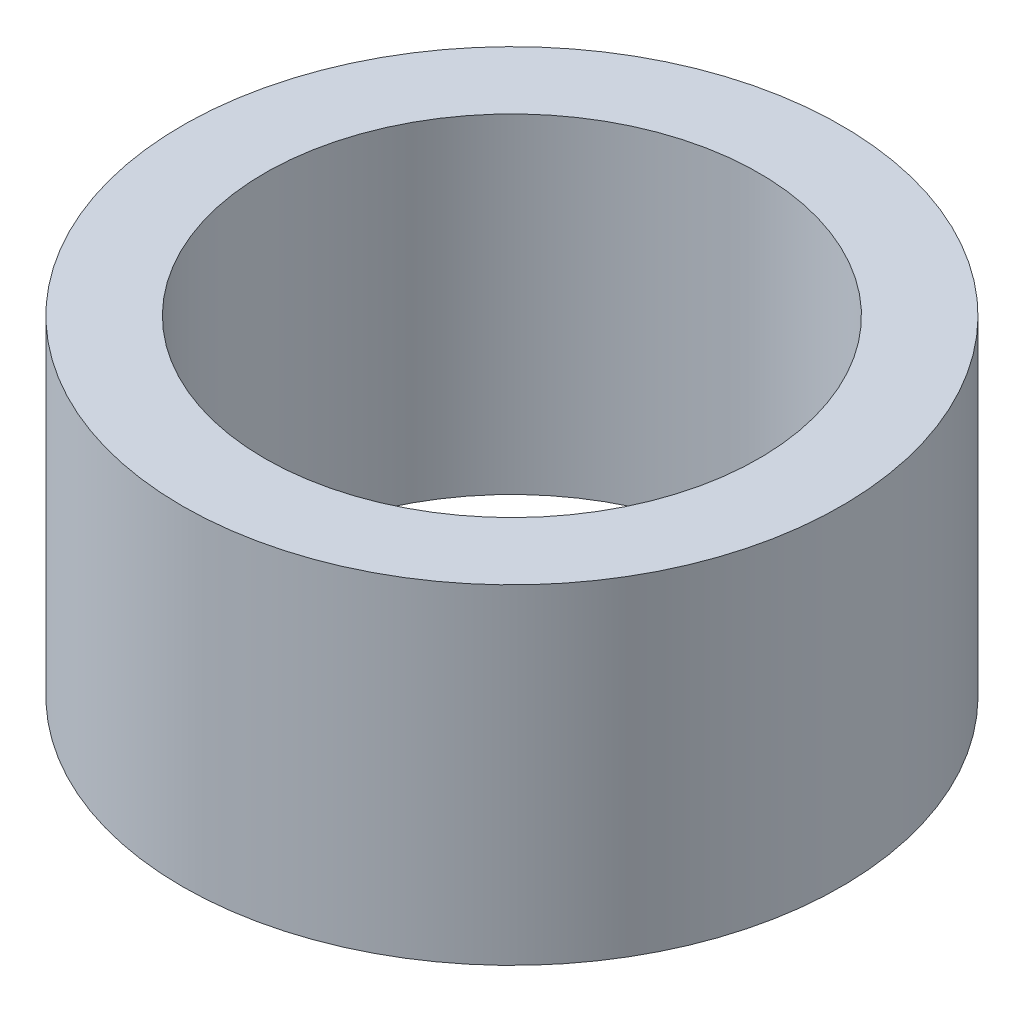
SolidWorks part; units mm, degrees
material "Malleable Cast Iron"
ref_plane "Front Plane" through (0, 0, 0) normal (0, 0, 1) x (1, 0, 0)
ref_plane "Top Plane" through (0, 0, 0) normal (0, 1, 0) x (1, 0, 0)
ref_plane "Right Plane" through (0, 0, 0) normal (1, 0, 0) x (0, 0, -1)
sketch "Sketch1" plane through (0, 0, 0) normal (0, 1, 0) x (1, 0, 0)
  circle A0 centre (0, 0) radius 30
  circle A1 centre (0, 0) radius 40
  dimension "D1" = 80
  dimension "D2" = 60
extrude "Boss-Extrude1" add sketch "Sketch1" along normal blind 40
